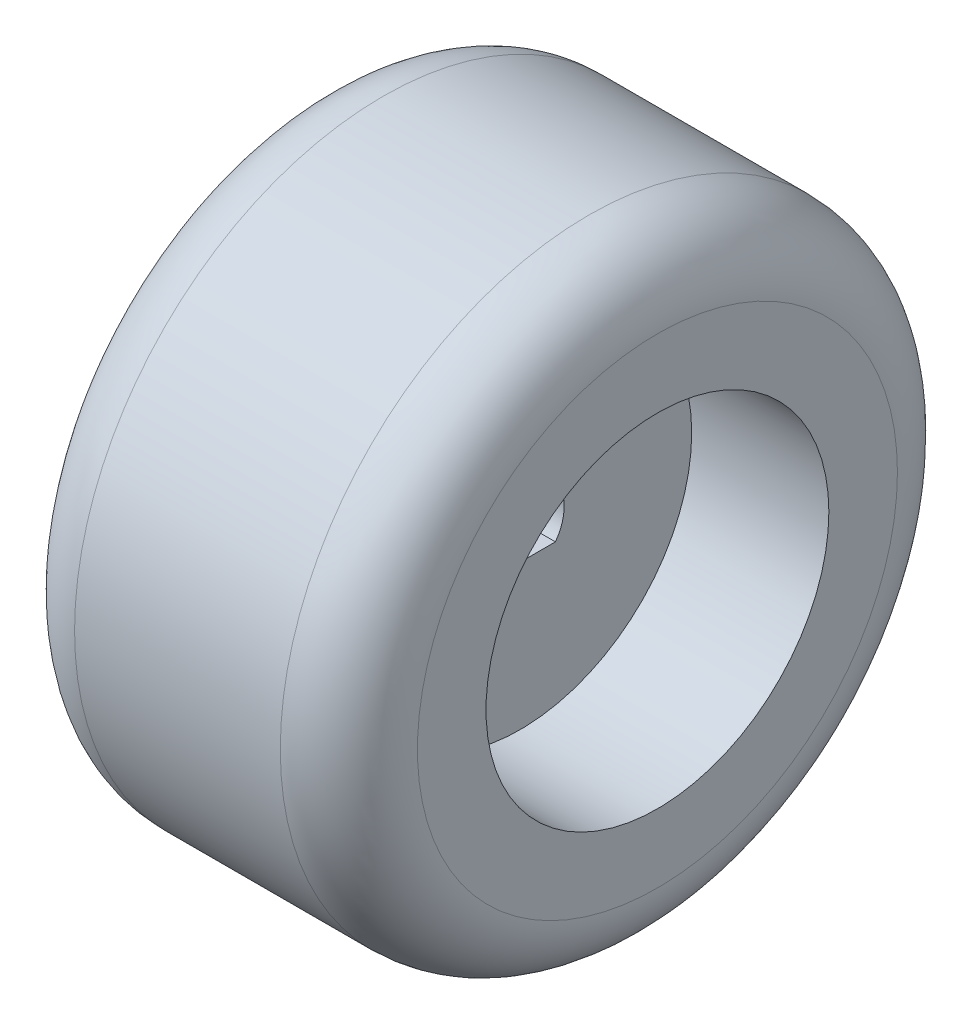
SolidWorks part; units mm, degrees
material "Corrugated Paper"
ref_plane "Front Plane" through (0, 0, 0) normal (0, 0, 1) x (1, 0, 0)
ref_plane "Top Plane" through (0, 0, 0) normal (0, 1, 0) x (1, 0, 0)
ref_plane "Right Plane" through (0, 0, 0) normal (1, 0, 0) x (0, 0, -1)
sketch "Sketch1" plane through (0, 0, 0) normal (1, 0, 0) x (0, 0, -1)
  circle A0 centre (0, 0) radius 22.5
  dimension "D1" = 45
extrude "Boss-Extrude1" add sketch "Sketch1" along normal blind 25
sketch "Sketch2" plane through (25, 0, 0) normal (1, 0, 0) x (0, 0, -1)
  circle A0 centre (0, 0) radius 12.5
  circle A1 centre (0, 0) radius 22.5 construction
  dimension "D1" = 10
extrude "Cut-Extrude1" cut sketch "Sketch2" against normal blind 10
fillet "Fillet1" radius 5 2 edges at (0, 0, -22.5) (25, 0, -22.5)
sketch "Sketch3" plane through (0, 0, 0) normal (-1, 0, 0) x (0, 0, 1)
  circle A0 centre (0, 0) radius 1.5
  dimension "D1" = 3
extrude "Cut-Extrude2" cut sketch "Sketch3" against normal through all
sketch "Sketch4" plane through (0, 0, 0) normal (-1, 0, 0) x (0, 0, 1)
  line L2 (-2.56, -1.92) -> (2.56, -1.92)
  line L3 (2.56, 1.92) -> (-2.56, 1.92)
  arc A2 (2.56, -1.92) -> (2.56, 1.92) centre (0, 0) ccw
  arc A3 (-2.56, 1.92) -> (-2.56, -1.92) centre (0, 0) ccw
extrude "Cut-Extrude3" cut sketch "Sketch4" against normal through all
